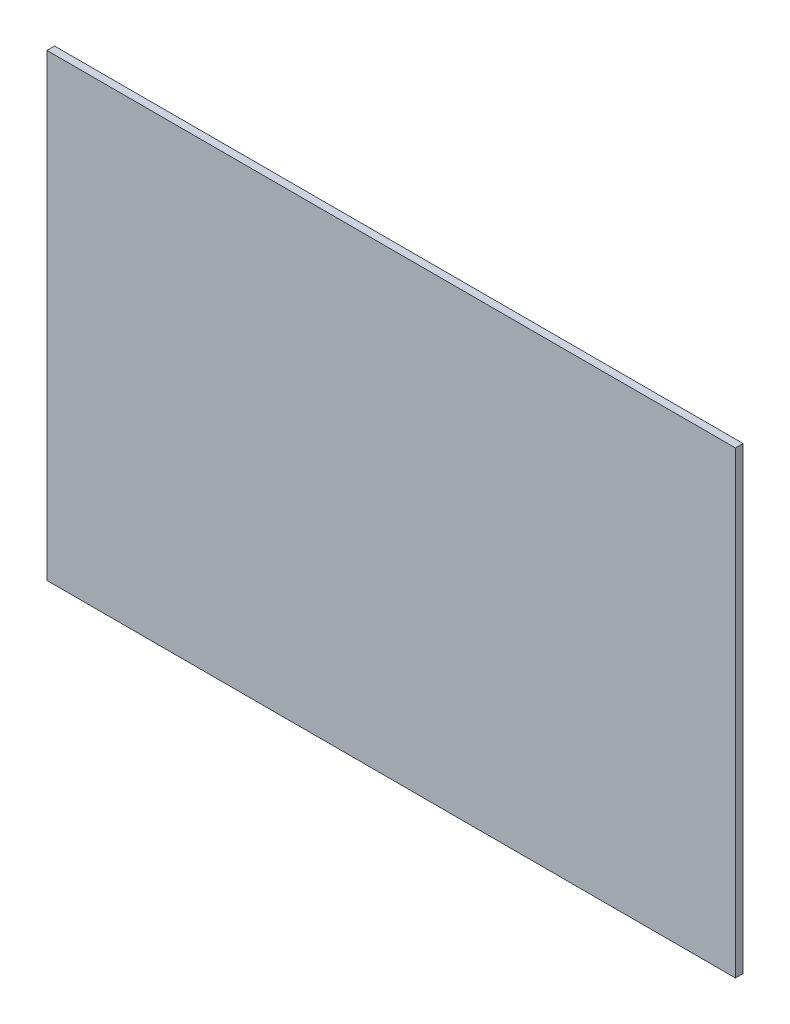
SolidWorks part; units mm, degrees
material "Vidro"
ref_plane "Plano frontal" through (0, 0, 0) normal (0, 0, 1) x (1, 0, 0)
ref_plane "Plano superior" through (0, 0, 0) normal (0, 1, 0) x (1, 0, 0)
ref_plane "Plano direito" through (0, 0, 0) normal (1, 0, 0) x (0, 0, -1)
sketch "Esboço1" plane through (0, 0, 0) normal (0, 0, 1) x (1, 0, 0)
  line L0 (0, 205.7443) -> (0, -205.7443) construction
  line L1 (-273.0159, 0) -> (273.0159, 0) construction
  line L2 (225, 150) -> (-225, 150)
  line L3 (-225, 150) -> (-225, -150)
  line L4 (225, -150) -> (-225, -150)
  line L5 (225, 150) -> (225, -150)
  dimension "D1" = 300
  dimension "D2" = 450
extrude "Ressalto-extrusão1" add sketch "Esboço1" along normal blind 5
